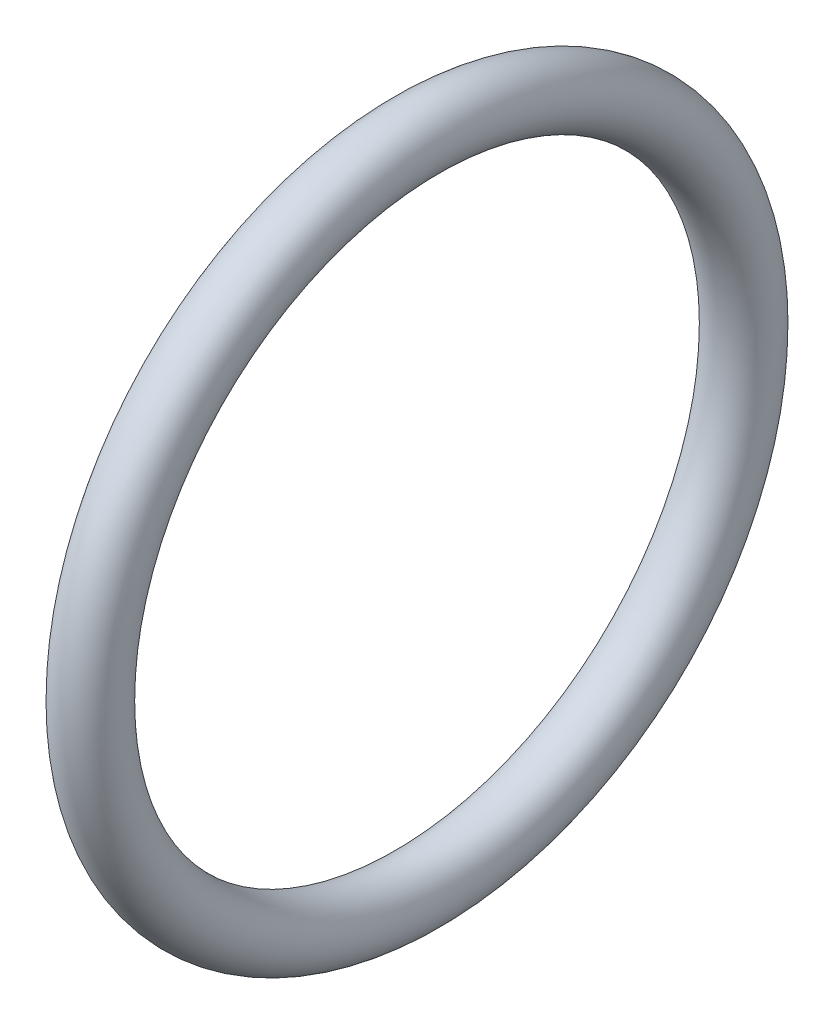
SolidWorks part; units mm, degrees
material "Резина"
ref_plane "Front Plane" through (0, 0, 0) normal (0, 0, 1) x (1, 0, 0)
ref_plane "Top Plane" through (0, 0, 0) normal (0, 1, 0) x (1, 0, 0)
ref_plane "Right Plane" through (0, 0, 0) normal (1, 0, 0) x (0, 0, -1)
sketch "Sketch1" plane through (0, 0, 0) normal (0, 0, 1) x (1, 0, 0)
  line L0 (-8.9776, 0) -> (8.9776, 0) construction
  line L8 (-10.818, 35) -> (-38.3014, 35)
  line L9 (-38.3014, 35) -> (-38.3014, 20)
  line L10 (-38.3014, 20) -> (11.6986, 20)
  line L11 (11.6986, 20) -> (11.6986, 22)
  line L12 (11.6986, 22) -> (4.6137, 26.0905)
  line L13 (4.6137, 26.0905) -> (3.8637, 24.7915)
  line L14 (-0.4664, 27.2915) -> (0.2836, 28.5905)
  line L15 (0.2836, 28.5905) -> (-10.818, 35)
  arc A1 (-0.4664, 27.2915) -> (3.8637, 24.7915) centre (1.6986, 26.0415) ccw
  circle A2 centre (1.6986, 26.0415) radius 2.5
  dimension "D1" = 0
revolve "Revolve1" add sketch "Sketch1" angle 360 about L0
